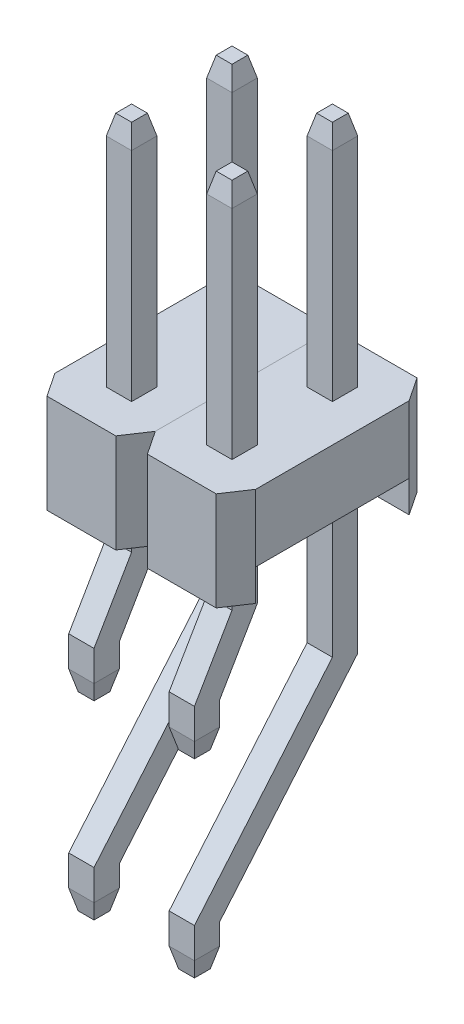
SolidWorks part; units mm, degrees
ref_plane "前视基准面" through (0, 0, 0) normal (0, 0, 1) x (1, 0, 0)
ref_plane "上视基准面" through (0, 0, 0) normal (0, 1, 0) x (1, 0, 0)
ref_plane "右视基准面" through (0, 0, 0) normal (1, 0, 0) x (0, 0, -1)
sketch "草图1" plane through (0, 0, 0) normal (0, 1, 0) x (1, 0, 0)
  line L0 (0, 0) -> (0, -2.54) construction
  line L1 (1.27, -2.54) -> (-1.27, -2.54)
  line L2 (1.27, -2.54) -> (1.27, 2.54)
  line L3 (1.27, 2.54) -> (-1.27, 2.54)
  line L4 (-1.27, -2.54) -> (-1.27, 2.54)
  line L5 (1.27, -2.54) -> (-1.27, 2.54) construction
  line L6 (1.27, 2.54) -> (-1.27, -2.54) construction
  line L7 (-1.27, 0) -> (1.27, 0)
  line L8 (-0.32, -1.59) -> (0.32, -1.59)
  line L9 (-0.32, -1.59) -> (-0.32, -0.95)
  line L10 (-0.32, -0.95) -> (0.32, -0.95)
  line L11 (0.32, -1.59) -> (0.32, -0.95)
  line L12 (-0.32, -1.59) -> (0.32, -0.95) construction
  line L13 (-0.32, -0.95) -> (0.32, -1.59) construction
  point P0 (0, 0)
  point P9 (0, -1.27)
  dimension "D1" = 5.08
  dimension "D2" = 2.54
  dimension "D3" = 1.27
  dimension "D4" = 0.64
  dimension "D5" = 45
extrude "凸台-拉伸1" add sketch "草图1" along normal blind 2.5 contours L7 L4 L1 L2 L11 L8 L9 L10
chamfer "倒角1" distance 0.4 distance2 0.6 1 edges at (1.27, 1.25, 2.54)
chamfer "倒角2" distance 0.6 distance2 0.4 1 edges at (-1.27, 1.25, 2.54)
sketch "草图4" plane through (0, 2.5, 0) normal (0, -1, 0) x (-1, 0, 0)
  line L0 (0.32, -1.59) -> (-0.32, -1.59) construction
  line L1 (0.32, -1.59) -> (-0.32, -1.59)
  line L2 (0.32, -1.59) -> (0.32, -0.95)
  line L3 (0.32, -0.95) -> (-0.32, -0.95)
  line L4 (-0.32, -1.59) -> (-0.32, -0.95)
sketch "草图5" plane through (1.27, 0, 0) normal (1, 0, 0) x (0, 0, -1)
  line L0 (-1.94, 2.5) -> (-1.94, 0) construction
  line L1 (0, 0) -> (-1.94, 0)
  line L2 (0, 0) -> (0, 0.8)
  line L3 (0, 0.8) -> (-1.94, 0.8)
  line L4 (-1.94, 0) -> (-1.94, 0.8)
  dimension "D1" = 0.8
extrude "切除-拉伸1" cut sketch "草图5" against normal blind 6
mirror "镜向1" about plane through (0, 2.5, 0) normal (0, 0, -1) of bodies 109 106
sketch "草图6" plane through (0, 0, 0) normal (1, 0, 0) x (0, 0, -1)
  line L0 (1.59, 2.5) -> (1.59, 0.8) construction
  line L1 (0.95, 2.5) -> (0.95, 0.8) construction
  line L2 (-0.95, 2.5) -> (-0.95, 0.8) construction
  line L3 (-1.59, 2.5) -> (-1.59, 0.8) construction
  line L4 (1.59, 2.5) -> (1.59, 0.8) construction
  line L5 (0.95, 2.5) -> (0.95, 0.8) construction
  line L6 (-0.95, 2.5) -> (-0.95, 0.8) construction
  line L7 (-1.59, 2.5) -> (-1.59, 0.8) construction
  line L8 (-1.94, 2.5) -> (1.94, 2.5) construction
  line L9 (-1.59, 8.5) -> (-0.95, 8.5)
  line L10 (-1.59, 8.5) -> (-1.59, -0.8)
  line L12 (-0.95, 8.5) -> (-0.95, -0.9729)
  line L13 (0.95, 8.5) -> (1.59, 8.5)
  line L14 (0.95, 8.5) -> (0.95, -3.1)
  line L16 (1.59, 8.5) -> (1.59, -3.3342)
  line L17 (-1.94, 0) -> (-2.54, 0) construction
  line L18 (-0.95, -0.9729) -> (-1.9, -2.6029)
  line L19 (-1.9, -2.6029) -> (-1.9, -3.7)
  line L20 (-1.9, -3.7) -> (-2.54, -3.7)
  line L21 (-2.54, -3.7) -> (-2.54, -2.43)
  line L22 (-2.54, -2.43) -> (-1.59, -0.8)
  line L23 (0.95, -3.1) -> (-2.54, -7.23)
  line L24 (-2.54, -7.23) -> (-2.54, -8.5)
  line L25 (-2.54, -8.5) -> (-1.9, -8.5)
  line L26 (-1.9, -8.5) -> (-1.9, -7.4642)
  line L27 (-1.9, -7.4642) -> (1.59, -3.3342)
  line L28 (1.94, 0) -> (2.54, 0) construction
  line L29 (-1.59, -0.8) -> (-0.95, -0.9729) construction
  line L30 (0.95, -3.1) -> (1.59, -3.3342) construction
  line L31 (-2.54, -7.23) -> (-1.9, -7.4642) construction
  line L32 (-2.54, -2.43) -> (-1.9, -2.6029) construction
  line L33 (-2.54, 0) -> (-2.54, 2.5) construction
  line L34 (-2.065, -1.615) -> (-1.5121, -1.9373) construction
  line L35 (-0.155, -5.3992) -> (-0.6438, -4.9861) construction
  line L36 (2.54, 0) -> (2.54, 2.5) construction
  point P44 (-1.459, -2.3465)
  point P45 (0.95, -2.964)
  point P46 (-1.9, -2.6825)
  dimension "D1" = 6
  dimension "D2" = 90
  dimension "D3" = 3.7
  dimension "D4" = 8.5
  dimension "D5" = 90
  dimension "D6" = 0.8
  dimension "D7" = 0.6
  dimension "D8" = 1.27
extrude "凸台-拉伸3" add sketch "草图6" along normal mid plane 0.64
chamfer "倒角3" distance 0.5 distance2 0.12 8 edges at (0, 8.5, 0.95) (0.32, 8.5, 1.27) (0, 8.5, 1.59) (-0.32, 8.5, 1.27) (0, 8.5, -1.59) (0.32, 8.5, -1.27) (0, 8.5, -0.95) (-0.32, 8.5, -1.27)
chamfer "倒角4" distance 0.5 distance2 0.12 8 edges at (0, -3.7, 2.54) (0.32, -3.7, 2.22) (0, -3.7, 1.9) (-0.32, -3.7, 2.22) (0, -8.5, 2.54) (0.32, -8.5, 2.22) (0, -8.5, 1.9) (-0.32, -8.5, 2.22)
pattern_linear "阵列(线性)1" count 2 spacing 2.54 along (-1, 0, 0) of bodies 110
